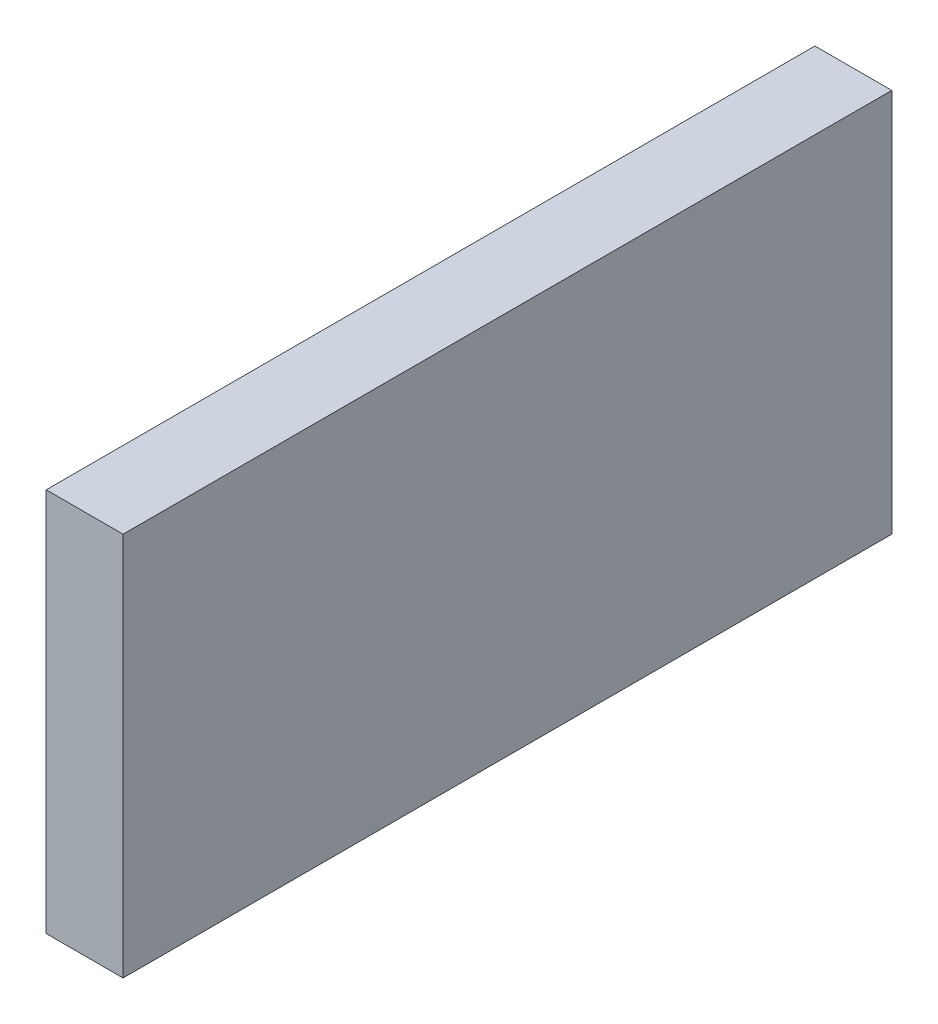
SolidWorks part; units mm, degrees
ref_plane "Front Plane" through (0, 0, 0) normal (0, 0, 1) x (1, 0, 0)
ref_plane "Top Plane" through (0, 0, 0) normal (0, 1, 0) x (1, 0, 0)
ref_plane "Right Plane" through (0, 0, 0) normal (1, 0, 0) x (0, 0, -1)
sketch "Sketch1" plane through (0, 0, 0) normal (1, 0, 0) x (0, 0, -1)
  line L1 (0, 0) -> (40, 0)
  line L2 (0, 0) -> (0, 20)
  line L3 (0, 20) -> (40, 20)
  line L4 (40, 0) -> (40, 20)
extrude "Boss-Extrude1" add sketch "Sketch1" against normal blind 4
